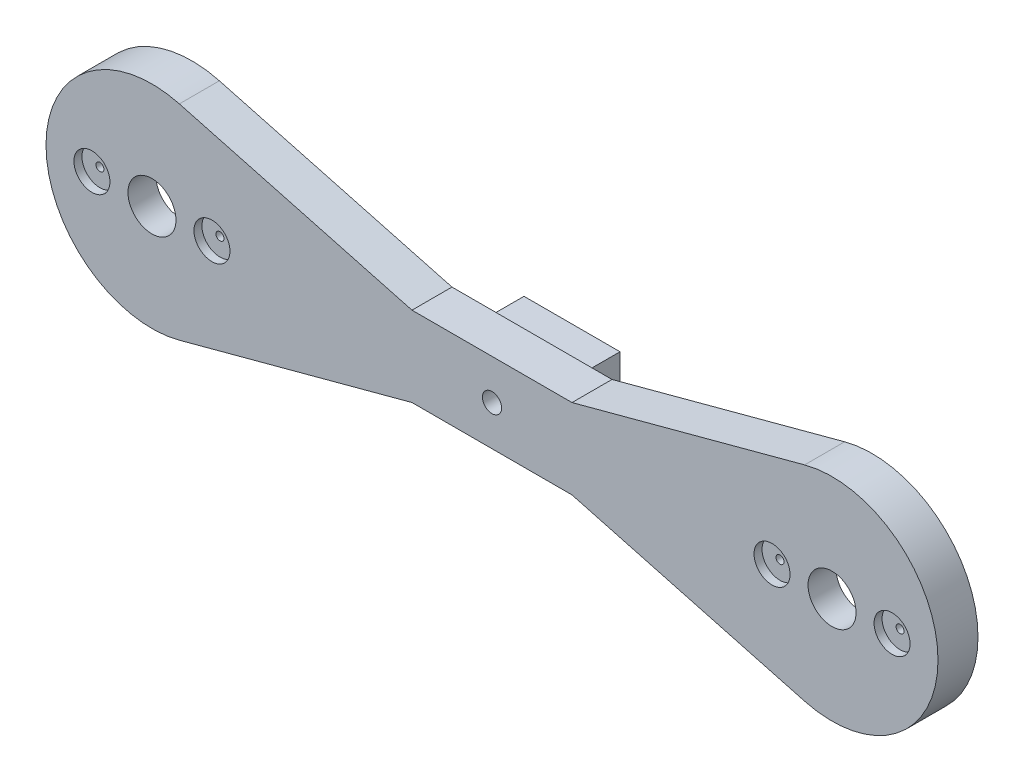
SolidWorks part; units mm, degrees
ref_plane "前视基准面" through (0, 0, 0) normal (0, 0, 1) x (1, 0, 0)
ref_plane "上视基准面" through (0, 0, 0) normal (0, 1, 0) x (1, 0, 0)
ref_plane "右视基准面" through (0, 0, 0) normal (1, 0, 0) x (0, 0, -1)
sketch "草图1" plane through (0, 0, 0) normal (0, 0, 1) x (1, 0, 0)
  line L0 (0, 0) -> (91.8, 0) construction
  line L1 (0, 0) -> (0, -78) construction
  line L2 (-10, 5) -> (10, 5)
  line L3 (10, 5) -> (39.0729, 12.7901)
  line L4 (-10, 5) -> (-39.0729, 12.7901)
  line L5 (10, -5) -> (39.0729, -12.7901)
  line L6 (-10, -5) -> (10, -5)
  line L7 (-10, -5) -> (-39.0729, -12.7901)
  arc A0 (-39.0729, 12.7901) -> (-39.0729, -12.7901) centre (-42.5, 0) ccw
  arc A1 (39.0729, 12.7901) -> (39.0729, -12.7901) centre (42.5, 0) cw
  circle A2 centre (-42.5, 0) radius 3
  circle A3 centre (42.5, 0) radius 3
  point P18 (0, 5)
  dimension "D6" = 6
  dimension "D7" = 6
  dimension "D8" = 13.2412
  dimension "D1" = 10
  dimension "D2" = 165
  dimension "D3" = 165
  dimension "D4" = 20
  dimension "D5" = 85
extrude "凸台-拉伸1" add sketch "草图1" along normal blind 5
sketch "草图3" plane through (0, 0, 0) normal (0, 0, -1) x (-1, 0, 0)
  line L1 (-5, 2.5) -> (5, 2.5)
  line L2 (-5, 2.5) -> (-5, -2.5)
  line L3 (-5, -2.5) -> (5, -2.5)
  line L4 (5, 2.5) -> (5, -2.5)
  line L6 (39.0729, 12.7901) -> (10, 5)
  line L7 (10, 5) -> (-10, 5)
  line L8 (-10, 5) -> (-39.0729, 12.7901)
  line L9 (-39.0729, -12.7901) -> (-10, -5)
  line L10 (-10, -5) -> (10, -5)
  line L11 (10, -5) -> (39.0729, -12.7901)
  line L12 (39.0729, 12.7901) -> (10, 5)
  line L13 (10, 5) -> (-10, 5)
  line L14 (-10, 5) -> (-39.0729, 12.7901)
  line L15 (-39.0729, -12.7901) -> (-10, -5)
  line L16 (-10, -5) -> (10, -5)
  line L17 (10, -5) -> (39.0729, -12.7901)
  arc A2 (-39.0729, 12.7901) -> (-39.0729, -12.7901) centre (-42.5, 0) ccw
  arc A3 (39.0729, -12.7901) -> (39.0729, 12.7901) centre (42.5, 0) ccw
  arc A4 (-39.0729, 12.7901) -> (-39.0729, -12.7901) centre (-42.5, 0) ccw
  arc A5 (39.0729, -12.7901) -> (39.0729, 12.7901) centre (42.5, 0) ccw
  dimension "D2" = 10
  dimension "D3" = 5
  dimension "D4" = 5
  dimension "D5" = 2.5
  dimension "D1" = 0
extrude "拉伸-薄壁1" add sketch "草图3" along normal blind 5 thin contours L4 L1 L2 L3
sketch "草图4" plane through (0, 0, 0) normal (0, 0, -1) x (-1, 0, 0)
  line L4 (5, -2.5) -> (5, 2.5)
  line L5 (5, 2.5) -> (-5, 2.5)
  line L6 (-5, 2.5) -> (-5, -2.5)
  line L7 (-5, -2.5) -> (5, -2.5)
  line L8 (5, -2.5) -> (5, 2.5)
  line L9 (5, 2.5) -> (-5, 2.5)
  line L10 (-5, 2.5) -> (-5, -2.5)
  line L11 (-5, -2.5) -> (5, -2.5)
  circle A0 centre (0, 0) radius 1.2
  dimension "D2" = 2.4
  dimension "D1" = 0
extrude "切除-拉伸2" cut sketch "草图4" against normal up to next contours A0
sketch "草图5" plane through (0, 0, 0) normal (0, 0, -1) x (-1, 0, 0)
  circle A0 centre (-42.5, 0) radius 9
  circle A1 centre (42.5, 0) radius 9
extrude "切除-拉伸3" cut sketch "草图5" against normal blind 1.5
sketch "草图6" plane through (0, 0, 1.5) normal (0, 0, -1) x (-1, 0, 0)
  circle A0 centre (-50, 0) radius 0.5
  circle A1 centre (-42.5, 0) radius 3 construction
  circle A2 centre (-35, 0) radius 0.5
  circle A3 centre (35, 0) radius 0.5
  circle A4 centre (50, 0) radius 0.5
  dimension "D1" = 7.5
  dimension "D2" = 7.5
extrude "切除-拉伸4" cut sketch "草图6" against normal blind 5
sketch "草图7" plane through (0, 0, 5) normal (0, 0, 1) x (1, 0, 0)
  circle A0 centre (-50, 0) radius 2.25
  circle A1 centre (-35, 0) radius 2.25
  circle A2 centre (35, 0) radius 2.25
  circle A3 centre (50, 0) radius 2.25
  dimension "D1" = 4.5
extrude "切除-拉伸5" cut sketch "草图7" against normal blind 1
